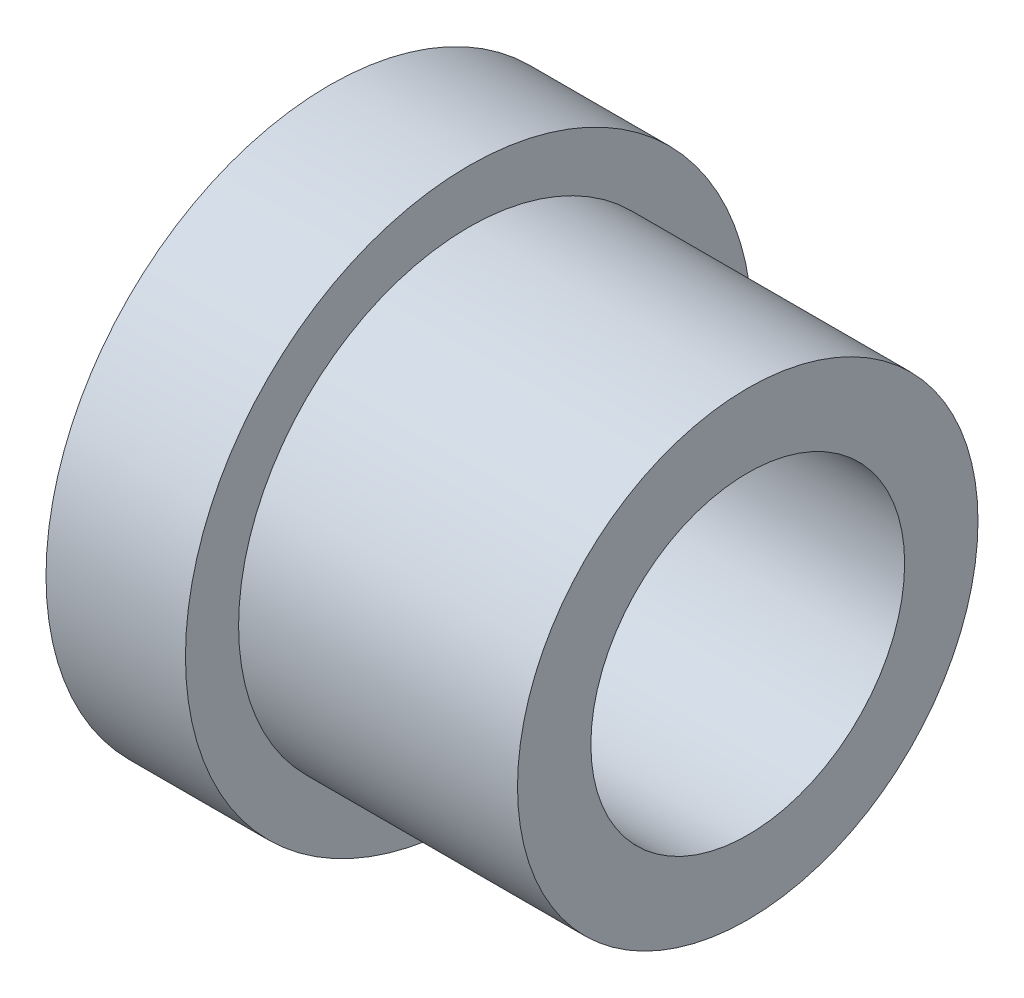
SolidWorks part; units mm, degrees
ref_plane "Front Plane" through (0, 0, 0) normal (0, 0, 1) x (1, 0, 0)
ref_plane "Top Plane" through (0, 0, 0) normal (0, 1, 0) x (1, 0, 0)
ref_plane "Right Plane" through (0, 0, 0) normal (1, 0, 0) x (0, 0, -1)
sketch "Sketch1" plane through (0, 0, 0) normal (0, 1, 0) x (1, 0, 0)
  line L0 (0, 0) -> (46.1936, 0) construction
  line L1 (0, 5) -> (0, 20.32)
  line L2 (0, 20.32) -> (10, 20.32)
  line L3 (10, 20.32) -> (10, 16.51)
  line L4 (10, 16.51) -> (30, 16.51)
  line L5 (30, 16.51) -> (30, 11.25)
  line L6 (30, 11.25) -> (13.5, 11.25)
  line L7 (13.5, 11.25) -> (13.5, 8.6)
  line L8 (13.5, 8.6) -> (12, 8.6)
  line L9 (12, 8.6) -> (12, 5)
  line L10 (12, 5) -> (0, 5)
  dimension "D1" = 20.32
  dimension "D2" = 16.51
  dimension "D3" = 10
  dimension "D4" = 20
  dimension "D5" = 11.25
  dimension "D6" = 8.6
  dimension "D7" = 5
  dimension "D8" = 1.5
  dimension "D9" = 12
revolve "Revolve1" add sketch "Sketch1" angle 360 about L0
